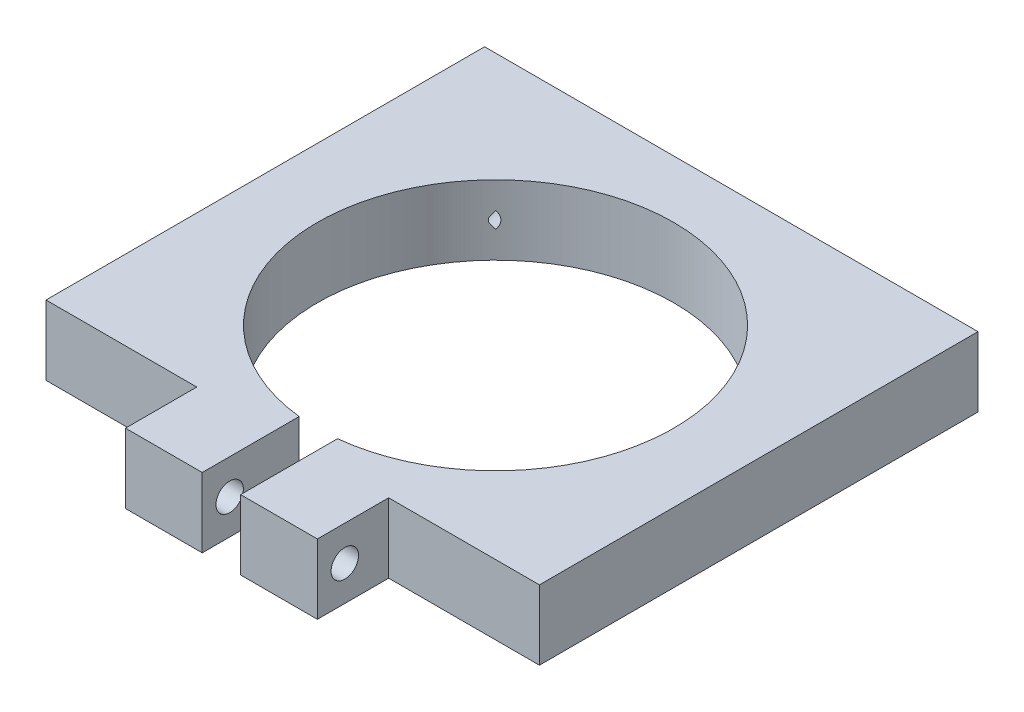
SolidWorks part; units mm, degrees
ref_plane "Plano frontal" through (0, 0, 0) normal (0, 0, 1) x (1, 0, 0)
ref_plane "Plano superior" through (0, 0, 0) normal (0, 1, 0) x (1, 0, 0)
ref_plane "Plano direito" through (0, 0, 0) normal (1, 0, 0) x (0, 0, -1)
sketch "Esboço1" plane through (0, 0, 0) normal (0, 1, 0) x (1, 0, 0)
  line L0 (45, 46.5) -> (-45, -46.5) construction
  line L1 (-45, 46.5) -> (45, 46.5)
  line L2 (-45, 46.5) -> (-45, -46.5)
  line L3 (-45, -46.5) -> (45, -46.5)
  line L4 (45, 46.5) -> (45, -46.5)
  dimension "D1" = 90
  dimension "D2" = 93
extrude "Ressalto-extrusão1" add sketch "Esboço1" along normal blind 12.7 contours L2 L3 L4 L1
sketch "Esboço3" plane through (0, 12.7, 0) normal (0, 1, 0) x (1, 0, 0)
  line L0 (-45, -46.5) -> (45, -46.5) construction
  line L1 (45, 46.5) -> (45, -46.5) construction
  circle A0 centre (0, 3.5) radius 32.51
  dimension "D1" = 65.02
  dimension "D2" = 50
  dimension "D3" = 45
extrude "Corte-extrusão2" cut sketch "Esboço3" against normal through all
sketch "Esboço5" plane through (0, 12.7, 0) normal (0, 1, 0) x (1, 0, 0)
  line L0 (0, -46.5) -> (0, -37.4552) construction
  line L1 (45, -46.5) -> (17.5, -46.5)
  line L2 (45, -46.5) -> (45, -33.5)
  line L3 (45, -33.5) -> (17.5, -33.5)
  line L4 (17.5, -46.5) -> (17.5, -33.5)
  line L5 (-45, -46.5) -> (-17.5, -46.5)
  line L6 (-45, -46.5) -> (-45, -33.5)
  line L7 (-45, -33.5) -> (-17.5, -33.5)
  line L8 (-17.5, -46.5) -> (-17.5, -33.5)
  line L9 (-45, -46.5) -> (45, -46.5) construction
  dimension "D1" = 17.5
  dimension "D2" = 17.5
  dimension "D3" = 13
  dimension "D4" = 13
extrude "Corte-extrusão4" cut sketch "Esboço5" against normal up to next
sketch "Esboço6" plane through (0, 12.7, 0) normal (0, 1, 0) x (1, 0, 0)
  line L1 (0, 0) -> (0, -46.5) construction
  line L2 (-17.5, -46.5) -> (17.5, -46.5) construction
  line L4 (3.5, -46.5) -> (-3.5, -46.5)
  line L5 (3.5, -46.5) -> (3.5, -20.1703)
  line L6 (3.5, -20.1703) -> (-3.5, -20.1703)
  line L7 (-3.5, -46.5) -> (-3.5, -20.1703)
  dimension "D1" = 3.5
  dimension "D2" = 3.5
extrude "Corte-extrusão5" cut sketch "Esboço6" against normal up to next
sketch "Esboço7" plane through (-17.5, 0, 0) normal (-1, 0, 0) x (0, 0, 1)
  line L0 (46.5, 12.7) -> (36.5, 0) construction
  line L1 (46.5, 0) -> (33.5, 0) construction
  circle A0 centre (41.5, 6.35) radius 2.5
  dimension "D2" = 5
  dimension "D1" = 10
extrude "Corte-extrusão6" cut sketch "Esboço7" against normal up to surface (35 mm away) up to face at (17.5, 6.35, 40)
hole_wizard "Taladro de margen para #00001" positions "Croquis2" profile "Croquis1" hole size "#0000" standard "Pulgada Ansi"
sketch "Croquis2" plane through (0, 0, -46.5) normal (0, 0, -1) x (-1, 0, 0)
  line L0 (-45, 12.7) -> (-45, 0) construction
  line L1 (45, 12.7) -> (45, 0) construction
  point P1 (-40, 6.35)
  point P4 (-25, 6.35)
  point P7 (40, 6.35)
  point P10 (25, 6.35)
  point P15 (-45, 6.35)
  dimension "D1" = 5
  dimension "D2" = 20
  dimension "D3" = 20
  dimension "D4" = 5
sketch "Croquis1" plane through (40, 6.35, -46.5) normal (1, 0, 0) x (0, 1, 0)
  line L0 (0, 0) -> (0, 21.5022)
  line L1 (0, 21.5022) -> (2.5, 20)
  line L2 (2.5, 20) -> (2.5, 0)
  line L5 (2.5, 0) -> (0, 0)
  line L10 (0, 21.5022) -> (-2.5, 20) construction
  line L11 (0, -6.35) -> (0, 107.95) construction
  dimension "Diámetro de taladro" = 5
  dimension "Profundidad de taladro" = 20
  dimension "Ángulo de perforador" = 118
